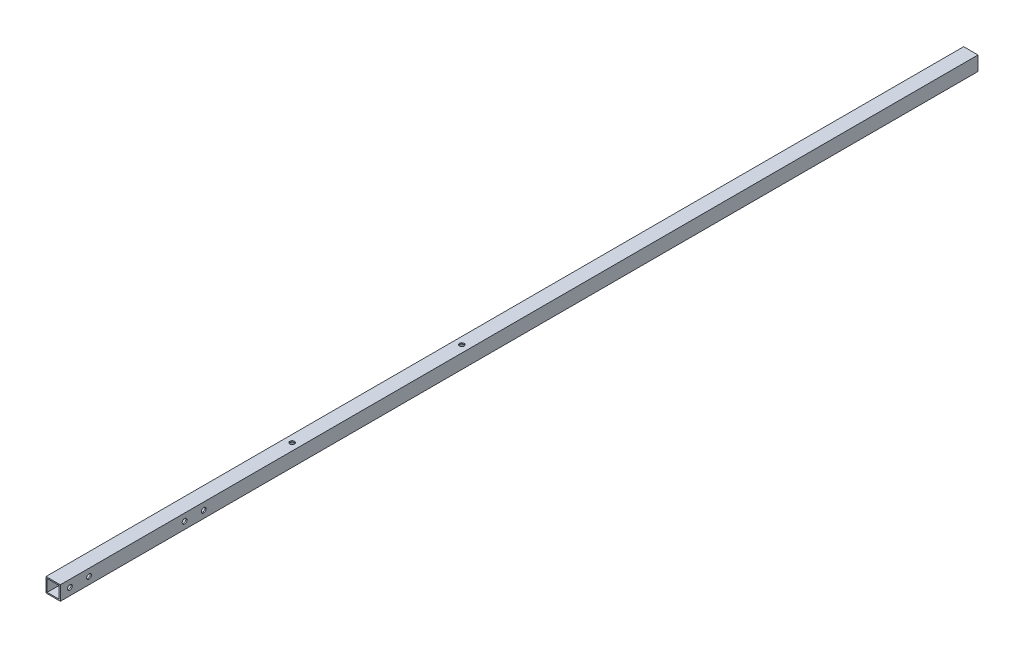
SolidWorks part; units mm, degrees
material "6061 Alloy"
ref_plane "Front Plane" through (0, 0, 0) normal (0, 0, 1) x (1, 0, 0)
ref_plane "Top Plane" through (0, 0, 0) normal (0, 1, 0) x (1, 0, 0)
ref_plane "Right Plane" through (0, 0, 0) normal (1, 0, 0) x (0, 0, -1)
sketch "Sketch1" plane through (0, 0, 0) normal (0, 0, 1) x (1, 0, 0)
  line L1 (-7.9375, -7.9375) -> (7.9375, -7.9375)
  line L2 (-7.9375, -7.9375) -> (-7.9375, 7.9375)
  line L3 (-7.9375, 7.9375) -> (7.9375, 7.9375)
  line L4 (7.9375, -7.9375) -> (7.9375, 7.9375)
  line L5 (-7.9375, -7.9375) -> (7.9375, 7.9375) construction
  line L6 (-7.9375, 7.9375) -> (7.9375, -7.9375) construction
  line L7 (-9.525, -9.525) -> (9.525, -9.525)
  line L8 (-9.525, -9.525) -> (-9.525, 9.525)
  line L9 (-9.525, 9.525) -> (9.525, 9.525)
  line L10 (9.525, -9.525) -> (9.525, 9.525)
  line L11 (-9.525, -9.525) -> (9.525, 9.525) construction
  line L12 (-9.525, 9.525) -> (9.525, -9.525) construction
  point P0 (0, 0)
  point P6 (0, 0)
  dimension "D1" = 19.05
  dimension "D2" = 19.05
  dimension "D3" = 1.5875
  dimension "D4" = 1.5875
extrude "Boss-Extrude1" add sketch "Sketch1" along normal mid plane 1219.2
sketch "Sketch3" plane through (9.525, 0, 0) normal (1, 0, 0) x (0, 0, -1)
  line L0 (-609.6, 0) -> (-596.9, 0) construction
  line L1 (-609.6, -9.525) -> (-609.6, 9.525) construction
  line L2 (-609.6, 0) -> (-571.5, 0) construction
  circle A0 centre (-571.5, 0) radius 3.175
  circle A1 centre (-596.9, 0) radius 3.175
extrude "Cut-Extrude1" cut sketch "Sketch3" against normal through all
sketch "Sketch4" plane through (-9.525, 0, 0) normal (-1, 0, 0) x (0, 0, 1)
  line L0 (419.1, 0) -> (609.6, 0) construction
  line L1 (609.6, 0) -> (444.5, 0) construction
  line L3 (609.6, 9.525) -> (609.6, -9.525) construction
  circle A0 centre (444.5, 0) radius 3.175
  circle A1 centre (419.1, 0) radius 3.175
extrude "Cut-Extrude2" cut sketch "Sketch4" against normal through all
sketch "Sketch7" plane through (0, -9.525, 0) normal (0, -1, 0) x (1, 0, 0)
  line L0 (0, 609.6) -> (0, 292.1) construction
  line L1 (0, 609.6) -> (0, 66.675) construction
  circle A0 centre (0, 292.1) radius 3.175
  circle A1 centre (0, 66.675) radius 3.175
extrude "Cut-Extrude4" cut sketch "Sketch7" against normal through all and the other way through all
